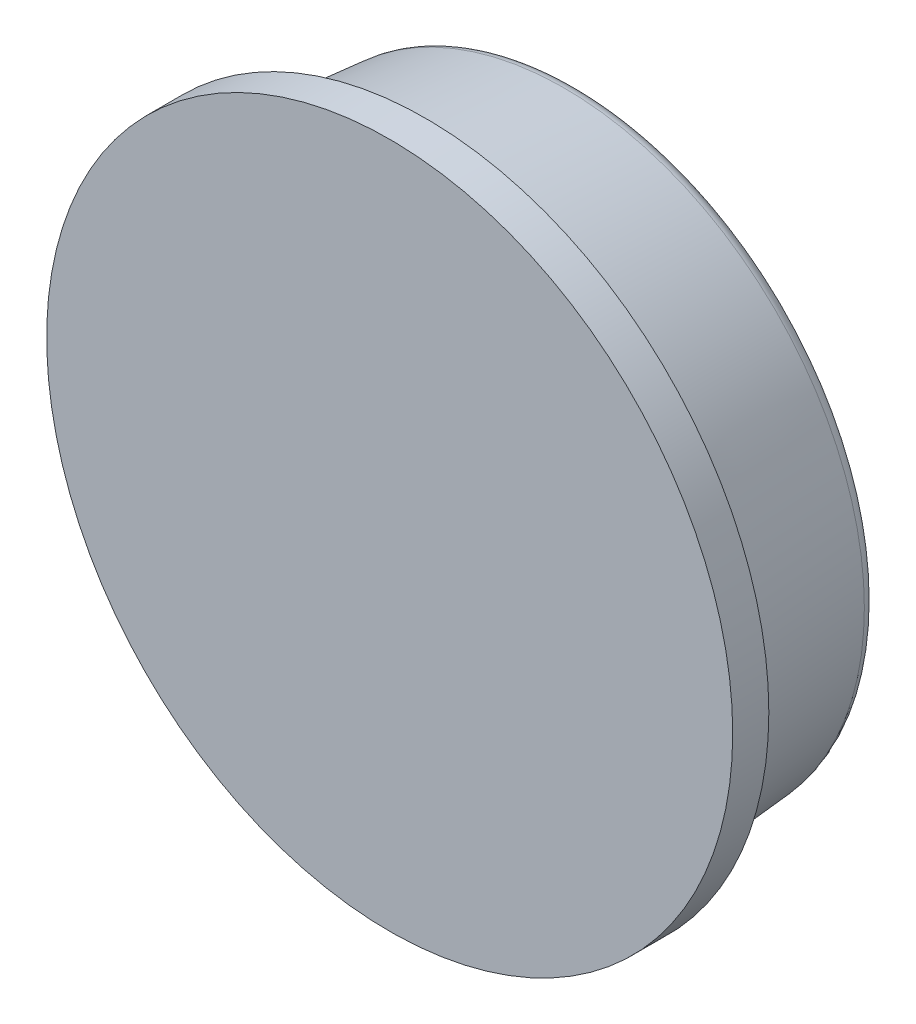
SolidWorks part; units mm, degrees
ref_plane "Front Plane" through (0, 0, 0) normal (0, 0, 1) x (1, 0, 0)
ref_plane "Top Plane" through (0, 0, 0) normal (0, 1, 0) x (1, 0, 0)
ref_plane "Right Plane" through (0, 0, 0) normal (1, 0, 0) x (0, 0, -1)
sketch "Sketch1" plane through (0, 0, 0) normal (0, 0, 1) x (1, 0, 0)
  circle A0 centre (0, 0) radius 5.2578
  dimension "D1" = 10.5156
ref_plane "Plane1" through (0, 0, 3.302) normal (0, 0, 1) x (1, 0, 0)
sketch "Sketch2" plane through (0, 0, 3.302) normal (0, 0, 1) x (1, 0, 0)
  circle A0 centre (0, 0) radius 6.0325
  dimension "D1" = 12.065
extrude "Boss-Extrude1" add sketch "Sketch2" against normal blind 0.635 contours A0
sketch "Sketch3" plane through (0, 0, 2.667) normal (0, 0, -1) x (-1, 0, 0)
  circle A0 centre (0, 0) radius 5.4864
  dimension "D1" = 10.9728
loft "Loft1" add profiles "Sketch1", "Sketch3"
fillet "Fillet1" radius 0.254 1 edges at (5.2578, 0, 0)
